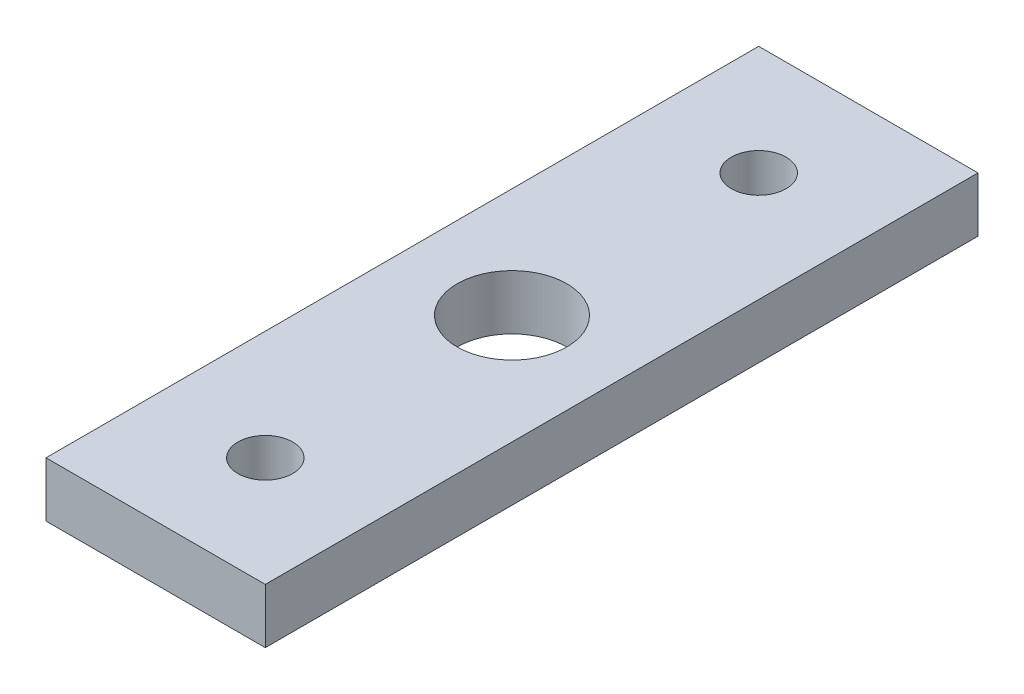
SolidWorks part; units mm, degrees
material "1023 Carbon Steel Sheet (SS)"
ref_plane "Front Plane" through (0, 0, 0) normal (0, 0, 1) x (1, 0, 0)
ref_plane "Top Plane" through (0, 0, 0) normal (0, 1, 0) x (1, 0, 0)
ref_plane "Right Plane" through (0, 0, 0) normal (1, 0, 0) x (0, 0, -1)
sketch "Sketch1" plane through (0, 0, 0) normal (0, 1, 0) x (1, 0, 0)
  line L1 (-12.7, 41.275) -> (12.7, 41.275)
  line L2 (-12.7, 41.275) -> (-12.7, -41.275)
  line L3 (-12.7, -41.275) -> (12.7, -41.275)
  line L4 (12.7, 41.275) -> (12.7, -41.275)
  line L5 (0, -41.275) -> (0, 41.275) construction
  line L6 (-12.7, 0) -> (12.7, 0) construction
  circle A0 centre (0, 0) radius 6.35
  circle A1 centre (0, 28.575) radius 3.175
  circle A2 centre (0, -28.575) radius 3.175
  point P0 (0, 0)
  dimension "D3" = 12.7
  dimension "D5" = 6.35
  dimension "D1" = 82.55
  dimension "D2" = 25.4
  dimension "D4" = 12.7
extrude "Boss-Extrude1" add sketch "Sketch1" along normal blind 6.35
